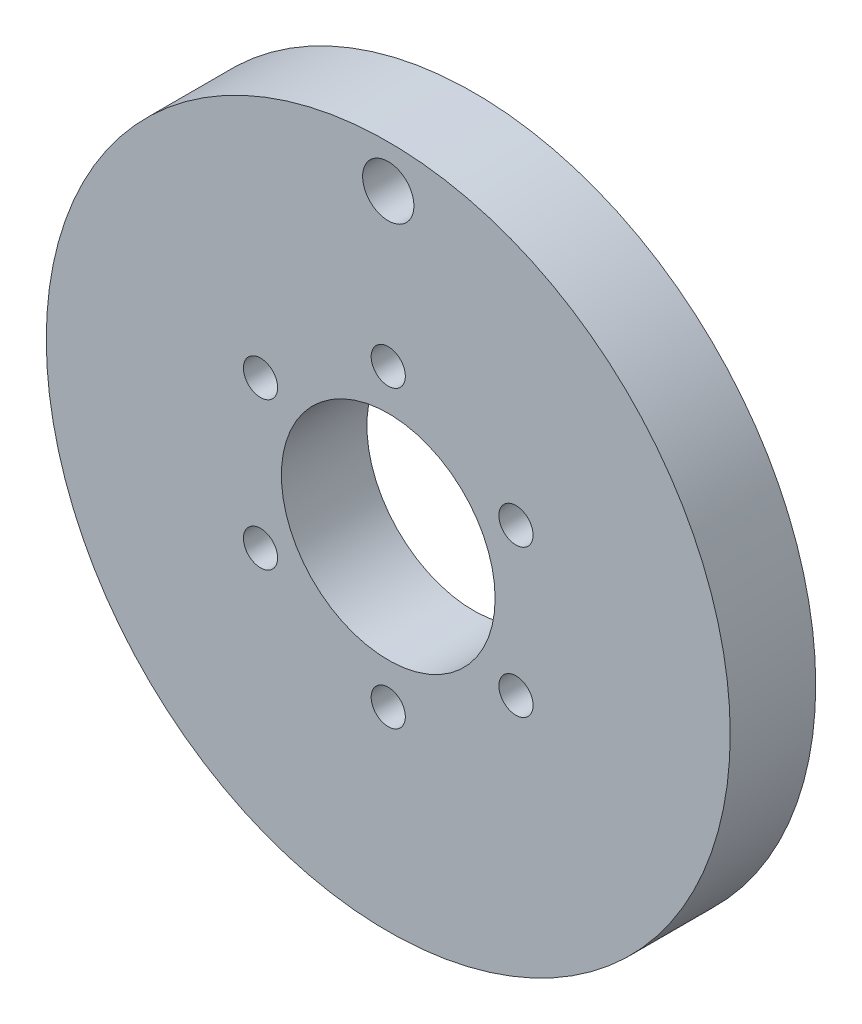
SolidWorks part; units mm, degrees
ref_plane "前视基准面" through (0, 0, 0) normal (0, 0, 1) x (1, 0, 0)
ref_plane "上视基准面" through (0, 0, 0) normal (0, 1, 0) x (1, 0, 0)
ref_plane "右视基准面" through (0, 0, 0) normal (1, 0, 0) x (0, 0, -1)
sketch "草图1" plane through (0, 0, 0) normal (0, 0, 1) x (1, 0, 0)
  circle A0 centre (-35.479, 11.8806) radius 17.25
  circle A1 centre (-35.479, 11.8806) radius 12.5
  circle A2 centre (-35.479, 11.8806) radius 40
  circle A3 centre (-35.479, 29.1306) radius 2
  circle A4 centre (-20.54, 20.5056) radius 2
  circle A5 centre (-20.54, 3.2556) radius 2
  circle A6 centre (-35.479, -5.3694) radius 2
  circle A7 centre (-50.4179, 3.2556) radius 2
  circle A8 centre (-50.4179, 20.5056) radius 2
  circle A9 centre (-35.479, 11.8806) radius 35
  circle A11 centre (-35.479, 46.8806) radius 3
  point P19 (-35.479, 11.8806)
  point P20 (0, 0)
  dimension "D1" = 34.5
  dimension "D2" = 80
  dimension "D3" = 25
  dimension "D4" = 6
  dimension "D5" = 35
extrude "凸台-拉伸1" add sketch "草图1" along normal blind 10 contours A2 A11 A9 | A11 A9 A8 A0 A3 A4 A5 A6 A7 | A8 A0 A7 A6 A5 A4 A3 A1 | A1
